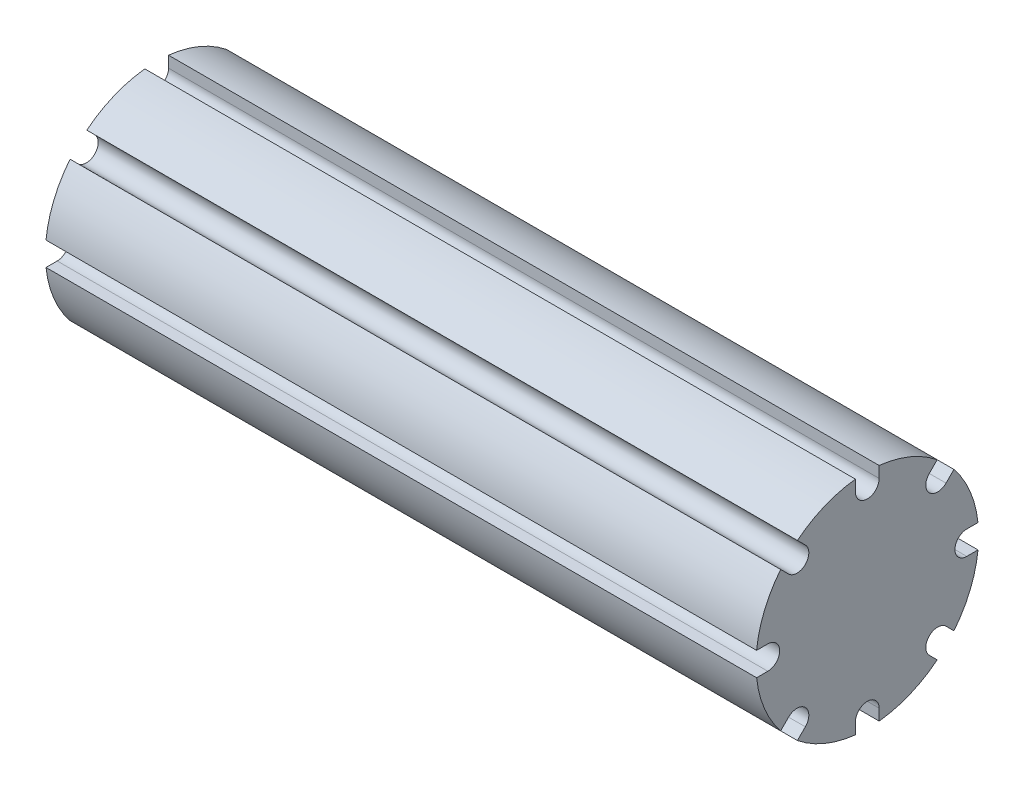
SolidWorks part; units mm, degrees
ref_plane "前视基准面" through (0, 0, 0) normal (0, 0, 1) x (1, 0, 0)
ref_plane "上视基准面" through (0, 0, 0) normal (0, 1, 0) x (1, 0, 0)
ref_plane "右视基准面" through (0, 0, 0) normal (1, 0, 0) x (0, 0, -1)
other "Configuration Table"
sketch "草图1" plane through (0, 0, 0) normal (1, 0, 0) x (0, 0, -1)
  circle A0 centre (0, 0) radius 23.5
  dimension "D1" = 47
extrude "凸台-拉伸1" add sketch "草图1" along normal mid plane 150
sketch "草图2" plane through (75, 0, 0) normal (1, 0, 0) x (0, 0, -1)
  line L2 (2.5, 21) -> (2.5, 23.3666)
  line L3 (-2.5, 21) -> (-2.5, 23.3666)
  arc A0 (-2.5, 21) -> (2.5, 21) centre (0, 21) ccw
  circle A2 centre (0, 0) radius 23.5 construction
  arc A4 (2.5, 23.3666) -> (-2.5, 23.3666) centre (0, 0) ccw
  arc A5 (-2.5, 21) -> (0, 23.5) centre (0, 21) ccw
  circle M5 centre (0, 0) radius 23.5
  dimension "D1" = 5
extrude "切除-拉伸1" cut sketch "草图2" against normal through all contours A0 A5 A4 L3 | A5 L2 M5
pattern_circular "阵列(圆周)2" count 8 over 360 about axis through (0, 0, 0) along (1, 0, 0) of "切除-拉伸1"
